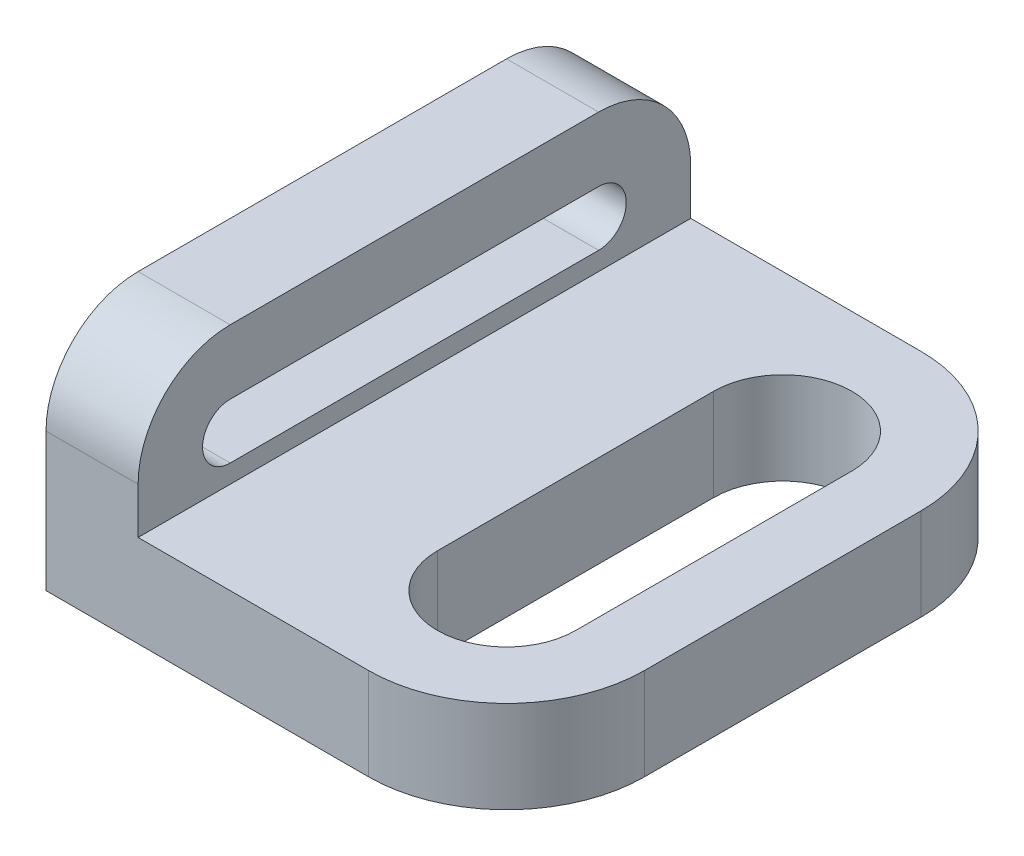
SolidWorks part; units mm, degrees
ref_plane "Front Plane" through (0, 0, 0) normal (0, 0, 1) x (1, 0, 0)
ref_plane "Top Plane" through (0, 0, 0) normal (0, 1, 0) x (1, 0, 0)
ref_plane "Right Plane" through (0, 0, 0) normal (1, 0, 0) x (0, 0, -1)
sketch "Sketch1" plane through (0, 0, 0) normal (1, 0, 0) x (0, 0, -1)
  line L0 (-40, 30) -> (40, 30) construction
  line L1 (-60, 0) -> (60, 0)
  line L2 (-60, 0) -> (-60, 30)
  line L3 (-40, 50) -> (40, 50)
  line L4 (60, 0) -> (60, 30)
  line L5 (-40, 36) -> (40, 36)
  line L6 (-40, 24) -> (40, 24)
  arc A0 (40, 50) -> (60, 30) centre (40, 30) cw
  arc A1 (-60, 30) -> (-40, 50) centre (-40, 30) cw
  arc A2 (-40, 36) -> (-40, 24) centre (-40, 30) ccw
  arc A3 (40, 24) -> (40, 36) centre (40, 30) ccw
  point P4 (0, 0)
  point P8 (60, 50)
  point P11 (-60, 50)
  point P14 (0, 30)
  dimension "D3" = 20
  dimension "D6" = 6
  dimension "D1" = 50
  dimension "D2" = 120
  dimension "D4" = 30
  dimension "D5" = 80
extrude "Boss-Extrude1" add sketch "Sketch1" along normal mid plane 20
sketch "Sketch2" plane through (0, 0, 0) normal (0, -1, 0) x (1, 0, 0)
  line L0 (60, -30) -> (60, 30) construction
  line L1 (10, -60) -> (60, -60)
  line L2 (10, -60) -> (10, 60)
  line L3 (10, 60) -> (60, 60)
  line L4 (90, -30) -> (90, 30)
  line L5 (45, -30) -> (45, 30)
  line L6 (75, -30) -> (75, 30)
  line L7 (-10, -40) -> (-10, 40) construction
  arc A0 (60, 60) -> (90, 30) centre (60, 30) cw
  arc A1 (60, -60) -> (90, -30) centre (60, -30) ccw
  arc A2 (45, -30) -> (75, -30) centre (60, -30) ccw
  arc A3 (75, 30) -> (45, 30) centre (60, 30) ccw
  point P5 (60, 0)
  point P10 (90, 60)
  dimension "D2" = 30
  dimension "D4" = 15
  dimension "D1" = 80
  dimension "D3" = 60
  dimension "D5" = 70
extrude "Boss-Extrude2" add sketch "Sketch2" against normal blind 20
